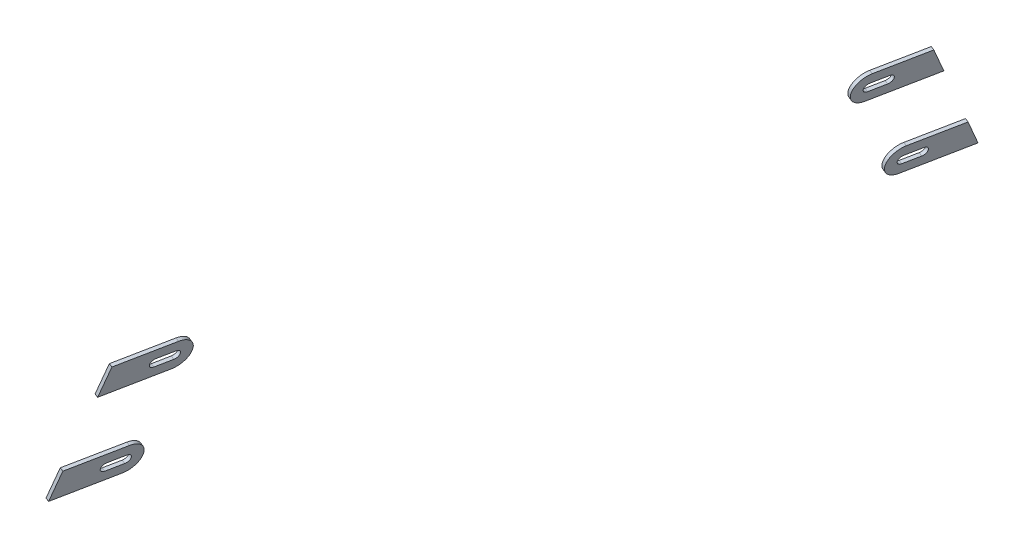
SolidWorks part; units mm, degrees
material "AISI 4130 Steel, normalized at 870C"
ref_plane "Front Plane" through (0, 0, 0) normal (0, 0, 1) x (1, 0, 0)
ref_plane "Top Plane" through (0, 0, 0) normal (0, 1, 0) x (1, 0, 0)
ref_plane "Right Plane" through (0, 0, 0) normal (1, 0, 0) x (0, 0, -1)
ref_plane "Plane1" through (-647.7275, 206.835, -128.8296) normal (0.936, -0.2989, 0.1862) x (0.1773, -0.0566, -0.9825)
ref_plane "Plane2" through (-659.6142, 210.6307, -131.1938) normal (-0.936, 0.2989, -0.1862) x (-0.1773, 0.0566, 0.9825)
sketch3d "3DSketch1"
  line L0 (-74.706, 1127.2095, -1532.204) -> (-334.6494, 378.679, -1427.0247) construction
  line L1 (-74.706, 1127.2095, -1532.204) -> (-240, 340, -1965) construction
  line L2 (-74.706, 1127.2095, -1532.204) -> (-334.6494, 378.679, -1427.0247) construction
  line L3 (-74.706, 1127.2095, -1532.204) -> (-240, 340, -1965) construction
  line L4 (-118.2147, 920, -1646.1247) -> (-146.6639, 920, -1503.0881) construction
  line L5 (-118.2147, 920, -1646.1247) -> (-146.6639, 920, -1503.0881) construction
sketch "Sketch2" plane through (-659.6142, 210.6307, -131.1938) normal (-0.936, 0.2989, -0.1862) x (-0.1773, 0.0566, 0.9825)
  line L0 (-1764.0306, 441.2698) -> (-1724.8204, 438.939)
  line L2 (-1723.7523, 456.9072) -> (-1754.4188, 458.7302)
  line L6 (-1544.2893, 840.4421) -> (-1398.708, 831.7881) construction
  line L7 (-1754.4188, 458.7302) -> (-1764.0306, 441.2698)
  line L8 (-1428.3419, 1051.0671) -> (-1868.8378, 250.8817) construction
  line L11 (-1759.2247, 450) -> (-1715.3022, 447.389) construction
  line L12 (-1734.2688, 448.5165) -> (-1724.2864, 447.9231) construction
  line L13 (-1734.1056, 451.2617) -> (-1724.1232, 450.6683)
  line L14 (-1734.4319, 445.7713) -> (-1724.4496, 445.178)
  arc A0 (-1723.7523, 456.9072) -> (-1724.8204, 438.939) centre (-1724.2864, 447.9231) cw
  arc A2 (-1734.1056, 451.2617) -> (-1734.4319, 445.7713) centre (-1734.2688, 448.5165) ccw
  arc A3 (-1724.4496, 445.178) -> (-1724.1232, 450.6683) centre (-1724.2864, 447.9231) ccw
  point P7 (-1759.2247, 450)
  point P14 (-1729.2776, 448.2198)
  point P21 (-1744.4255, 440.1044)
  dimension "D4" = 10
  dimension "D5" = 2.75
  dimension "D1" = 450
  dimension "D2" = 18
  dimension "D3" = 35
extrude "Boss-Extrude1" add sketch "Sketch2" along normal blind 2
sketch "Sketch4" plane through (-659.6142, 210.6307, -131.1938) normal (-0.936, 0.2989, -0.1862) x (-0.1773, 0.0566, 0.9825)
  line L0 (-1787.4483, 398.7302) -> (-1756.7202, 396.9036)
  line L1 (-1428.3419, 1051.0671) -> (-1868.8378, 250.8817) construction
  line L3 (-1757.7883, 378.9353) -> (-1797.0602, 381.2698)
  line L4 (-1797.0602, 381.2698) -> (-1787.4483, 398.7302)
  line L5 (-1544.2893, 840.4421) -> (-1398.708, 831.7881) construction
  line L6 (-1792.2542, 390) -> (-1748.2701, 387.3854) construction
  line L7 (-1767.2366, 388.5128) -> (-1757.2542, 387.9194) construction
  line L8 (-1767.0734, 391.258) -> (-1757.0911, 390.6646)
  line L9 (-1767.3998, 385.7677) -> (-1757.4174, 385.1743)
  arc A0 (-1756.7202, 396.9036) -> (-1757.7883, 378.9353) centre (-1757.2542, 387.9194) cw
  arc A1 (-1767.0734, 391.258) -> (-1767.3998, 385.7677) centre (-1767.2366, 388.5128) ccw
  arc A2 (-1757.4174, 385.1743) -> (-1757.0911, 390.6646) centre (-1757.2542, 387.9194) ccw
  point P10 (-1792.2542, 390)
  point P17 (-1762.2454, 388.2161)
  dimension "D3" = 35
  dimension "D5" = 2.75
  dimension "D1" = 18
  dimension "D2" = 390
  dimension "D4" = 10
extrude "Boss-Extrude2" add sketch "Sketch4" along normal blind 2 separate body
sketch "Sketch5" plane through (-659.6142, 210.6307, -131.1938) normal (-0.936, 0.2989, -0.1862) x (-0.1773, 0.0566, 0.9825)
  line L0 (-1428.3419, 1051.0671) -> (-1321.2913, 258.9362) construction
  line L1 (-1345.0029, 434.3926) -> (-1342.5463, 416.2148)
  line L2 (-1342.5463, 416.2148) -> (-1379.247, 418.3965)
  line L4 (-1378.1789, 436.3648) -> (-1345.0029, 434.3926)
  line L5 (-1544.2893, 840.4421) -> (-1398.708, 831.7881) construction
  line L6 (-1387.6971, 427.9147) -> (-1343.7746, 425.3037) construction
  line L7 (-1378.713, 427.3806) -> (-1368.7306, 426.7872) construction
  line L8 (-1378.5498, 430.1258) -> (-1368.5674, 429.5324)
  line L9 (-1378.8761, 424.6355) -> (-1368.8938, 424.0421)
  line L10 (-1715.3022, 447.389) -> (-1387.6971, 427.9147) construction
  arc A0 (-1378.1789, 436.3648) -> (-1379.247, 418.3965) centre (-1378.713, 427.3806) ccw
  arc A1 (-1378.5498, 430.1258) -> (-1378.8761, 424.6355) centre (-1378.713, 427.3806) ccw
  arc A2 (-1368.8938, 424.0421) -> (-1368.5674, 429.5324) centre (-1368.7306, 426.7872) ccw
  arc A3 (-1724.8204, 438.939) -> (-1723.7523, 456.9072) centre (-1724.2864, 447.9231) ccw construction
  point P0 (-1343.7746, 425.3037)
  point P16 (-1373.7218, 427.0839)
  dimension "D3" = 35
  dimension "D5" = 2.75
  dimension "D1" = 425.3037
  dimension "D2" = 18
  dimension "D4" = 10
extrude "Boss-Extrude3" add sketch "Sketch5" along normal blind 2 separate body
sketch "Sketch6" plane through (-659.6142, 210.6307, -131.1938) normal (-0.936, 0.2989, -0.1862) x (-0.1773, 0.0566, 0.9825)
  line L0 (-1428.3419, 1051.0671) -> (-1321.2913, 258.9362) construction
  line L1 (-1336.5612, 371.9274) -> (-1334.1046, 353.7496)
  line L2 (-1334.1046, 353.7496) -> (-1370.8053, 355.9312)
  line L4 (-1369.7372, 373.8995) -> (-1336.5612, 371.9274)
  line L5 (-1544.2893, 840.4421) -> (-1398.708, 831.7881) construction
  line L6 (-1748.2701, 387.3854) -> (-1379.2554, 365.4494) construction
  line L7 (-1370.2712, 364.9154) -> (-1360.2889, 364.322) construction
  line L8 (-1370.1081, 367.6605) -> (-1360.1257, 367.0671)
  line L9 (-1370.4344, 362.1702) -> (-1360.4521, 361.5768)
  arc A0 (-1369.7372, 373.8995) -> (-1370.8053, 355.9312) centre (-1370.2712, 364.9154) ccw
  arc A1 (-1757.7883, 378.9353) -> (-1756.7202, 396.9036) centre (-1757.2542, 387.9194) ccw construction
  arc A2 (-1370.1081, 367.6605) -> (-1370.4344, 362.1702) centre (-1370.2712, 364.9154) ccw
  arc A3 (-1360.4521, 361.5768) -> (-1360.1257, 367.0671) centre (-1360.2889, 364.322) ccw
  point P0 (-1335.3329, 362.8385)
  point P17 (-1365.2801, 364.6187)
  dimension "D4" = 2.75
  dimension "D1" = 18
  dimension "D2" = 35
  dimension "D3" = 10
extrude "Boss-Extrude4" add sketch "Sketch6" along normal blind 2 separate body
